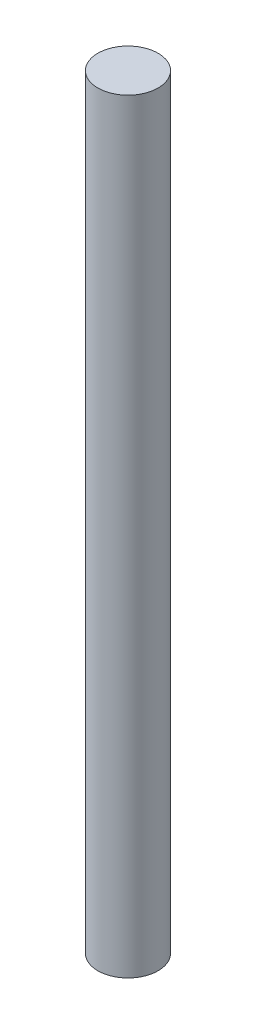
SolidWorks part; units mm, degrees
ref_plane "Front Plane" through (0, 0, 0) normal (0, 0, 1) x (1, 0, 0)
ref_plane "Top Plane" through (0, 0, 0) normal (0, 1, 0) x (1, 0, 0)
ref_plane "Right Plane" through (0, 0, 0) normal (1, 0, 0) x (0, 0, -1)
sketch "Sketch1" plane through (0, 0, 0) normal (0, 1, 0) x (1, 0, 0)
  circle A0 centre (0, 0) radius 20.0152
  dimension "D1" = 40.0304
extrude "Boss-Extrude1" add sketch "Sketch1" along normal blind 508
sketch "Sketch2" plane through (0, 0, 0) normal (0, -1, 0) x (1, 0, 0)
  circle A0 centre (0, 0) radius 12.7
  dimension "D1" = 25.4
extrude "Cut-Extrude1" cut sketch "Sketch2" against normal blind 25.4
